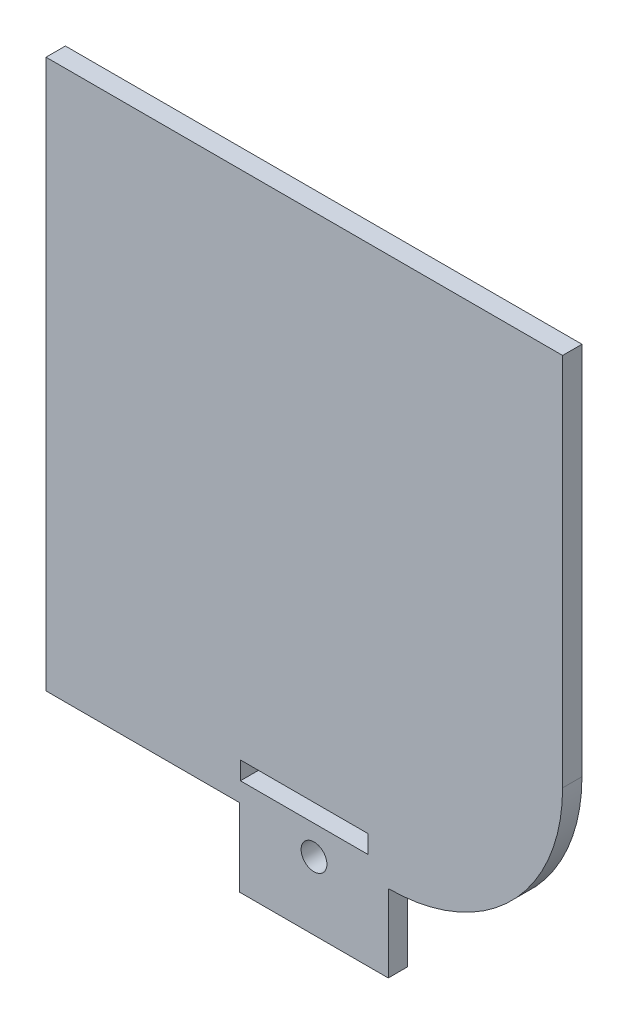
SolidWorks part; units mm, degrees
ref_plane "Front Plane" through (0, 0, 0) normal (0, 0, 1) x (1, 0, 0)
ref_plane "Top Plane" through (0, 0, 0) normal (0, 1, 0) x (1, 0, 0)
ref_plane "Right Plane" through (0, 0, 0) normal (1, 0, 0) x (0, 0, -1)
sketch "Croquis1" plane through (0, 0, 0) normal (0, 0, 1) x (1, 0, 0)
  line L0 (-40, 29) -> (-40, 0.0155) construction
  line L1 (-40, 29) -> (40, 29)
  line L3 (-10, -56) -> (13, -56) construction
  line L4 (40, 29) -> (40, -29)
  line L6 (0, 0) -> (40, 29) construction
  line L7 (-9.9, -50.2) -> (-9.9, -53)
  line L12 (-9.9, -53) -> (9.9, -53)
  line L13 (9.9, -53) -> (9.9, -50.2)
  line L14 (0, 0) -> (40, 0) construction
  line L15 (9.9, -50.2) -> (-9.9, -50.2)
  line L20 (0, 0) -> (0, -50.2) construction
  line L21 (-40, 29) -> (0, 0) construction
  line L23 (-10, -56) -> (-10, -68)
  line L24 (-10, -68) -> (13, -68)
  line L25 (13, -68) -> (13, -56)
  line L26 (1.5, -57.5) -> (1.5, -56) construction
  line L27 (-40, 29) -> (-40, -56)
  line L28 (-40, -56) -> (-10, -56)
  arc A9 (13, -56) -> (40, -29) centre (13, -29) ccw
  circle A10 centre (1.5, -57.5) radius 3 construction
  circle A11 centre (1.5, -57.5) radius 2
  point P0 (0, 0)
  point P37 (1.5, -54.5)
  dimension "D4" = 27
  dimension "D1" = 80
  dimension "D12" = 6
  dimension "D14" = 4
  dimension "D2" = 85
  dimension "D7" = 2.8
  dimension "D8" = 19.8
  dimension "D9" = 3
  dimension "D10" = 15
  dimension "D11" = 23
  dimension "D13" = 1.5
extrude "Saliente-Extruir1" add sketch "Croquis1" along normal blind 3
